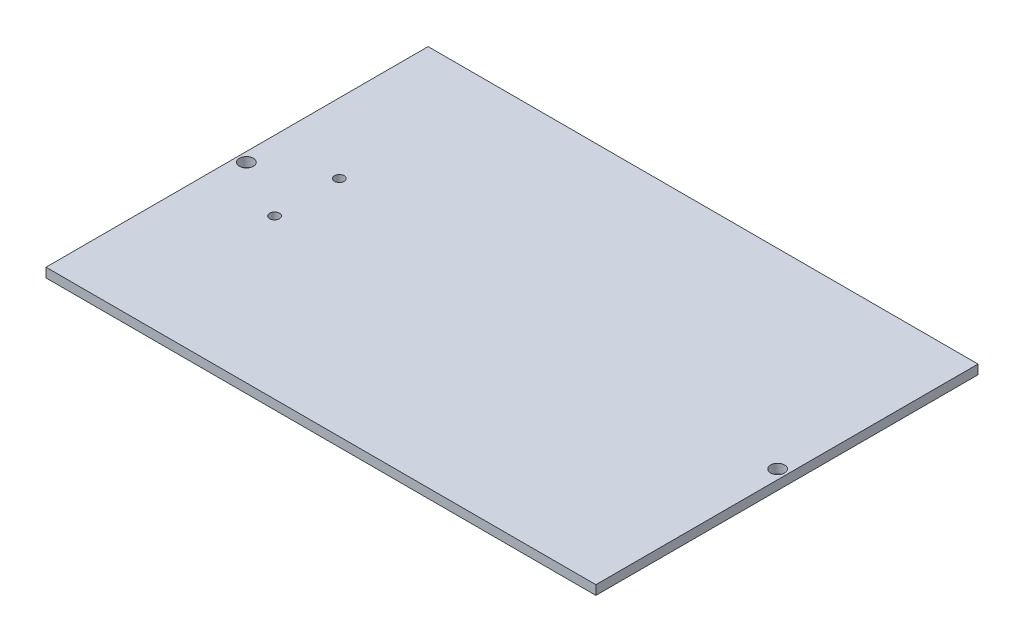
SolidWorks part; units mm, degrees
ref_plane "Front Plane" through (0, 0, 0) normal (0, 0, 1) x (1, 0, 0)
ref_plane "Top Plane" through (0, 0, 0) normal (0, 1, 0) x (1, 0, 0)
ref_plane "Right Plane" through (0, 0, 0) normal (1, 0, 0) x (0, 0, -1)
sketch "Sketch1" plane through (0, 0, 0) normal (0, 1, 0) x (1, 0, 0)
  line L1 (-59, -41) -> (59, -41)
  line L2 (-59, -41) -> (-59, 41)
  line L3 (-59, 41) -> (59, 41)
  line L4 (59, -41) -> (59, 41)
  line L5 (-59, -41) -> (59, 41) construction
  line L6 (-59, 41) -> (59, -41) construction
  point P0 (0, 0)
  dimension "D1" = 118
  dimension "D2" = 82
extrude "Boss-Extrude1" add sketch "Sketch1" along normal blind 2
sketch "Sketch2" plane through (0, 2, 0) normal (0, 1, 0) x (1, 0, 0)
  line L0 (-44, -8) -> (-44, 8)
  line L1 (-59, -41) -> (59, -41) construction
  line L2 (-59, 41) -> (-59, -41) construction
  circle A0 centre (-44, 6.95) radius 1.05
  circle A1 centre (-44, -6.95) radius 1.05
  point P6 (-44, 0)
  dimension "D1" = 2.1
  dimension "D2" = 2.1
  dimension "D3" = 16
  dimension "D4" = 41
  dimension "D5" = 15
extrude "Cut-Extrude1" cut sketch "Sketch2" against normal blind 2 contours L0 A0 | L0 A0 | L0 A1 | L0 A1
sketch "Sketch3" plane through (0, 2, 0) normal (0, 1, 0) x (1, 0, 0)
  line L0 (-57, 0) -> (-59, 0) construction
  line L1 (-59, 41) -> (-59, -41) construction
  line L2 (0, 10.7648) -> (0, -8.274) construction
  circle A0 centre (-57, 0) radius 1.5
  circle A1 centre (57, 0) radius 1.5
  dimension "D1" = 3
  dimension "D2" = 2
extrude "Cut-Extrude2" cut sketch "Sketch3" against normal blind 10
